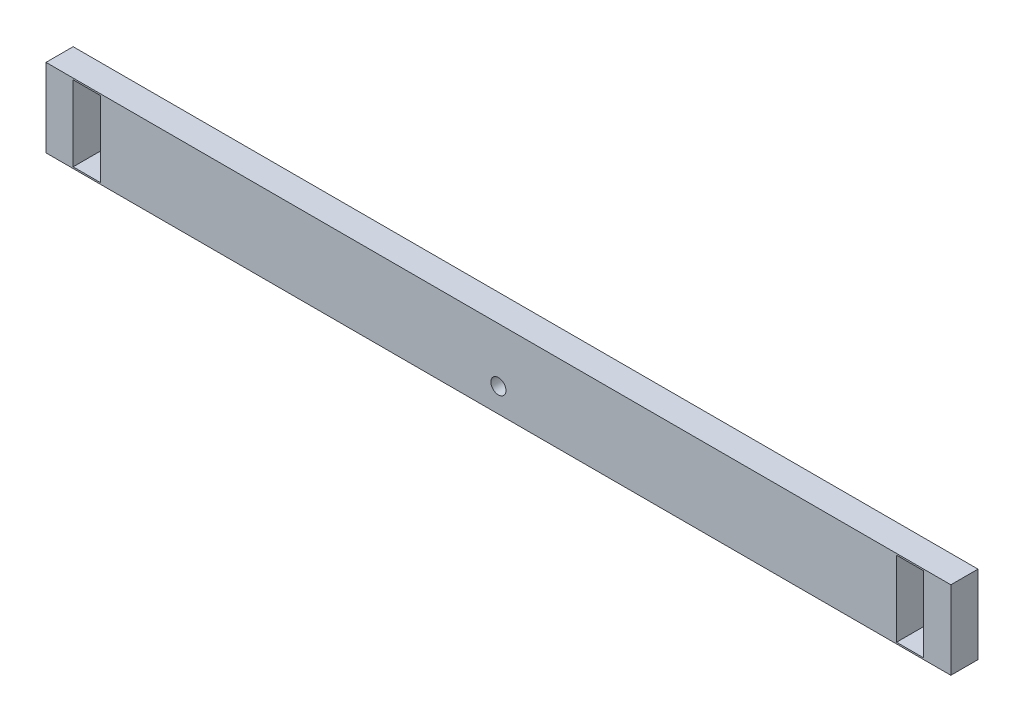
SolidWorks part; units mm, degrees
material "Maple"
ref_plane "Front Plane" through (0, 0, 0) normal (0, 0, 1) x (1, 0, 0)
ref_plane "Top Plane" through (0, 0, 0) normal (0, 1, 0) x (1, 0, 0)
ref_plane "Right Plane" through (0, 0, 0) normal (1, 0, 0) x (0, 0, -1)
sketch "Sketch1" plane through (0, 0, 0) normal (0, 0, 1) x (1, 0, 0)
  line L0 (300, 0) -> (300, -72) construction
  line L1 (0, 0) -> (600, 0)
  line L2 (0, 0) -> (0, -52)
  line L3 (0, -52) -> (257, -52)
  line L4 (600, 0) -> (600, -52)
  line L5 (600, -26) -> (0, -26) construction
  line L6 (307, -52) -> (600, -52)
  line L11 (582, -51) -> (564, -51)
  line L12 (18, -1) -> (36, -1)
  line L13 (18, -1) -> (18, -51)
  line L14 (18, -51) -> (36, -51)
  line L15 (36, -1) -> (36, -51)
  line L16 (18, -1) -> (36, -51) construction
  line L17 (18, -51) -> (36, -1) construction
  line L18 (564, -1) -> (564, -51)
  line L19 (582, -1) -> (564, -1)
  line L20 (582, -1) -> (582, -51)
  line L21 (307, -52) -> (257, -52)
  circle A0 centre (300, -36) radius 5
  point P10 (27, -26)
  point P22 (300, -63)
  dimension "D3" = 10
  dimension "D1" = 600
  dimension "D2" = 52
  dimension "D4" = 18
  dimension "D5" = 50
  dimension "D6" = 18
extrude "Boss-Extrude1" add sketch "Sketch1" along normal blind 18
